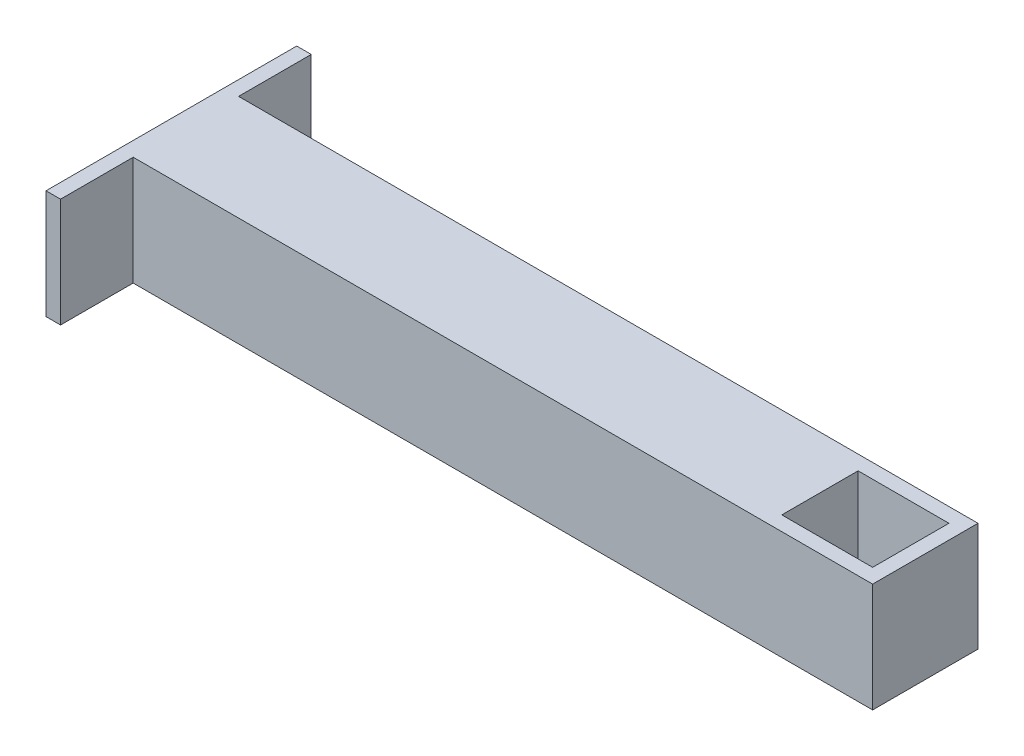
SolidWorks part; units mm, degrees
ref_plane "Front Plane" through (0, 0, 0) normal (0, 0, 1) x (1, 0, 0)
ref_plane "Top Plane" through (0, 0, 0) normal (0, 1, 0) x (1, 0, 0)
ref_plane "Right Plane" through (0, 0, 0) normal (1, 0, 0) x (0, 0, -1)
sketch "Sketch1" plane through (0, 0, 0) normal (0, 1, 0) x (1, 0, 0)
  line L1 (0, 0) -> (12.5, 0)
  line L2 (0, 0) -> (0, -10.5)
  line L3 (0, -10.5) -> (12.5, -10.5)
  line L4 (12.5, 0) -> (12.5, -10.5)
  line L5 (-2, -12.5) -> (14.5, -12.5)
  line L6 (14.5, 2) -> (14.5, -12.5)
  line L7 (-2, 2) -> (14.5, 2)
  line L8 (-2, 2) -> (-87.25, 2)
  line L9 (-87.25, 2) -> (-87.25, 12)
  line L10 (-87.25, 12) -> (-89.25, 12)
  line L11 (-89.25, 12) -> (-89.25, -22.5)
  line L12 (-89.25, -22.5) -> (-87.25, -22.5)
  line L13 (-87.25, -22.5) -> (-87.25, -12.5)
  line L14 (-87.25, -12.5) -> (-2, -12.5)
  line L15 (6.25, 0) -> (6.25, -10.5) construction
  line L17 (-2, 2) -> (-2, -12.5) construction
  dimension "D1" = 12.5
  dimension "D2" = 10.5
  dimension "D4" = 10
  dimension "D5" = 10
  dimension "D6" = 2
  dimension "D7" = 95.5
  dimension "D8" = 2
  dimension "D3" = 2
extrude "Boss-Extrude2" add sketch "Sketch1" along normal blind 15 contours L13 L14 L5 L6 L7 L8 L9 L10 L11 L12 L1 L4 L3 L2
